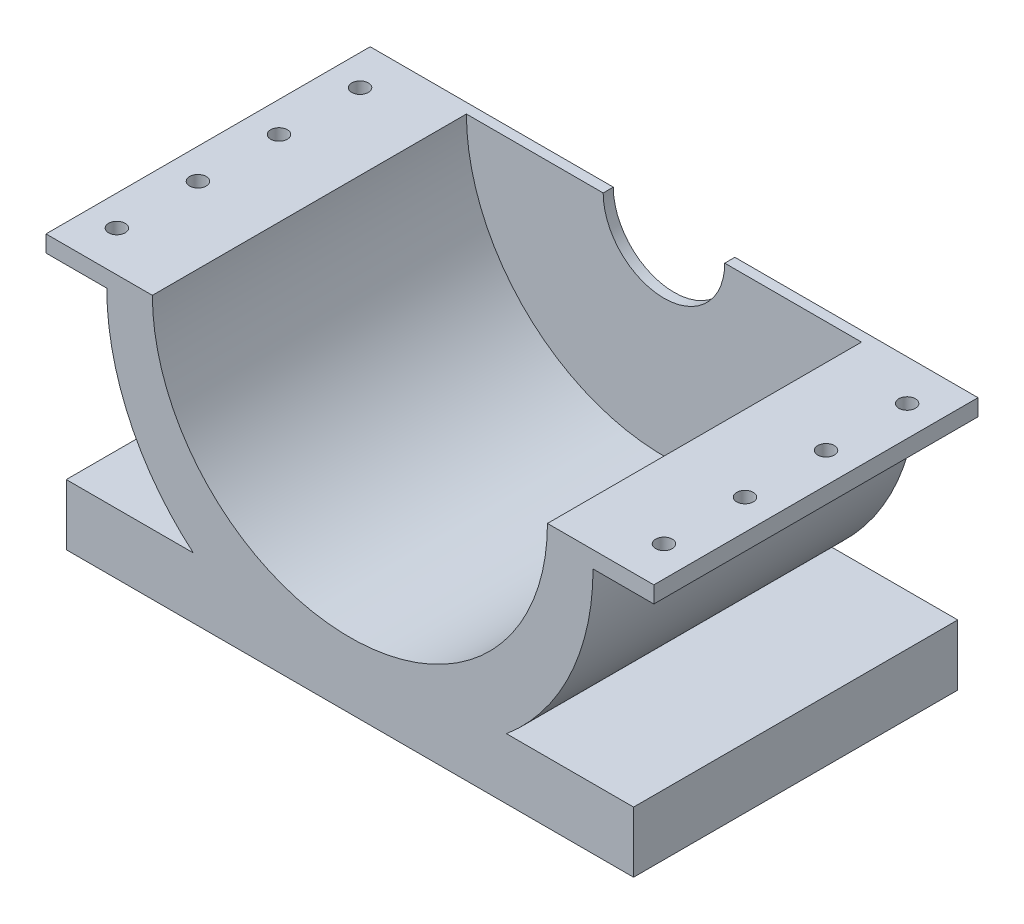
SolidWorks part; units mm, degrees
ref_plane "Front Plane" through (0, 0, 0) normal (0, 0, 1) x (1, 0, 0)
ref_plane "Top Plane" through (0, 0, 0) normal (0, 1, 0) x (1, 0, 0)
ref_plane "Right Plane" through (0, 0, 0) normal (1, 0, 0) x (0, 0, -1)
sketch "Sketch1" plane through (0, 0, 0) normal (0, 0, 1) x (1, 0, 0)
  line L0 (7.5, 0) -> (6, 0)
  line L1 (7.5, 0.41) -> (-7.5, 0.41)
  line L2 (-7.5, 0.41) -> (-7.5, 0)
  line L3 (7.5, 0.41) -> (7.5, 0)
  line L4 (-6, 0) -> (-7.5, 0)
  line L5 (7.5, 0) -> (-7.5, 0) construction
  line L6 (-7, -6.09) -> (7, -6.09)
  line L7 (-7, -4.59) -> (-3.8642, -4.59)
  line L8 (-7, -4.59) -> (-7, -6.09)
  line L9 (7, -4.59) -> (7, -6.09)
  line L10 (3.8642, -4.59) -> (7, -4.59)
  line L11 (-7, -4.59) -> (7, -4.59) construction
  arc A0 (-6, 0) -> (-3.8642, -4.59) centre (0, 0) ccw
  arc A1 (3.8642, -4.59) -> (6, 0) centre (0, 0) ccw
  point P6 (0, 0)
  point P12 (0, -6.09)
  dimension "D1" = 12
  dimension "D2" = 15
  dimension "D3" = 0.41
  dimension "D4" = 1.5
  dimension "D5" = 1.5
  dimension "D6" = 6.5
  dimension "D7" = 14
  dimension "D8" = 1.5
extrude "Boss-Extrude1" add sketch "Sketch1" along normal mid plane 8
sketch "Sketch2" plane through (0, 0, 4) normal (0, 0, 1) x (1, 0, 0)
  line L0 (7.5, 0.41) -> (-7.5, 0.41) construction
  line L1 (-4.875, 0.41) -> (4.875, 0.41)
  arc A0 (-4.875, 0.41) -> (4.875, 0.41) centre (0, 0.41) ccw
  dimension "D1" = 9.75
extrude "Cut-Extrude1" cut sketch "Sketch2" against normal blind 7.75
sketch "Sketch3" plane through (0, 0, -4) normal (0, 0, -1) x (-1, 0, 0)
  line L0 (-7.5, 0.41) -> (7.5, 0.41) construction
  line L1 (-1.5, 0.41) -> (1.5, 0.41)
  arc A0 (-1.5, 0.41) -> (1.5, 0.41) centre (0, 0.41) ccw
  dimension "D1" = 3
extrude "Cut-Extrude2" cut sketch "Sketch3" against normal blind 7.75
sketch "Sketch4" plane through (0, 0.41, 0) normal (0, 1, 0) x (1, 0, 0)
  line L0 (7.5, -4) -> (4.875, -4) construction
  line L2 (7.5, -4) -> (7.5, 4) construction
  circle A0 centre (6.75, 3) radius 0.205
  circle A1 centre (6.75, 1) radius 0.205
  circle A2 centre (6.75, -1) radius 0.205
  circle A3 centre (6.75, -3) radius 0.205
  point P12 (7.5, -3.0525)
  dimension "D1" = 0.41
  dimension "D2" = 0.41
  dimension "D3" = 0.41
  dimension "D4" = 0.41
  dimension "D5" = 1
  dimension "D6" = 0.75
  dimension "D7" = 2
  dimension "D8" = 2
  dimension "D9" = 2
extrude "Cut-Extrude3" cut sketch "Sketch4" against normal blind 2.75
mirror "Mirror1" about plane through (0, 0, 0) normal (1, 0, 0) of "Cut-Extrude3"
